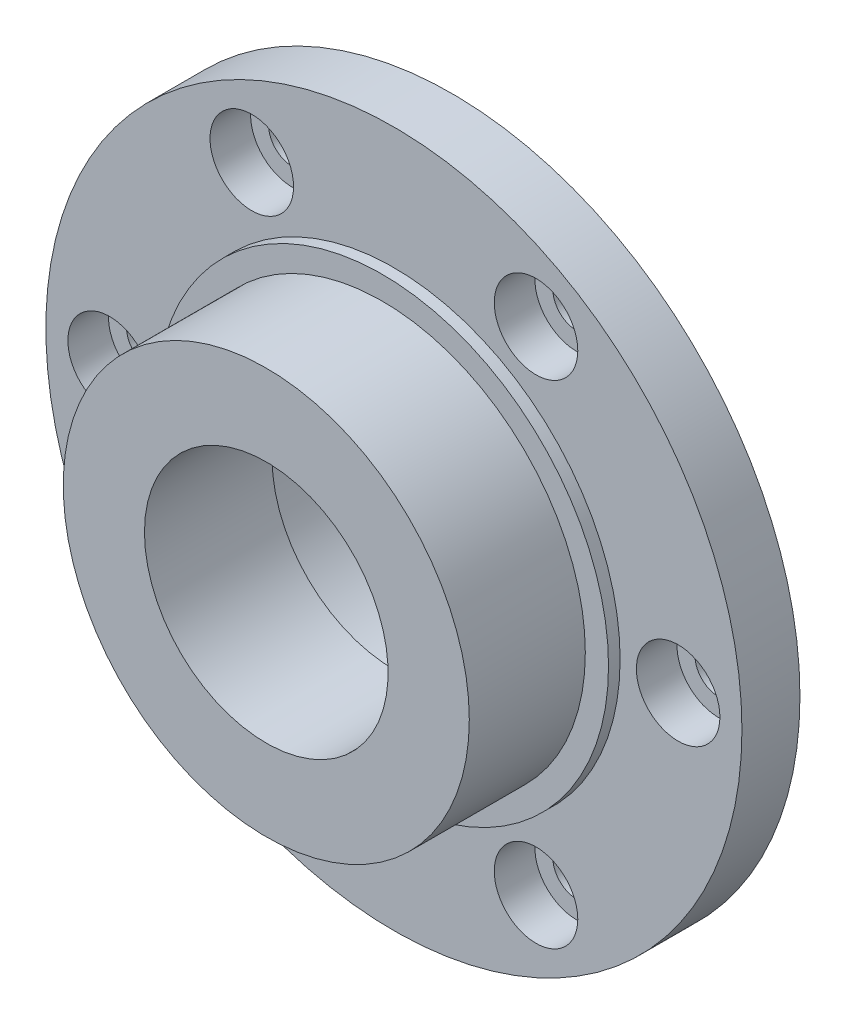
SolidWorks part; units mm, degrees
ref_plane "Front Plane" through (0, 0, 0) normal (0, 0, 1) x (1, 0, 0)
ref_plane "Top Plane" through (0, 0, 0) normal (0, 1, 0) x (1, 0, 0)
ref_plane "Right Plane" through (0, 0, 0) normal (1, 0, 0) x (0, 0, -1)
sketch "Sketch1" plane through (0, 0, 0) normal (0, 0, 1) x (1, 0, 0)
  circle A0 centre (0, 0) radius 30
  dimension "D1" = 60
extrude "Boss-Extrude1" add sketch "Sketch1" along normal blind 5
sketch "Sketch2" plane through (0, 0, 5) normal (0, 0, 1) x (1, 0, 0)
  circle A0 centre (0, 0) radius 19.5
  dimension "D1" = 39
extrude "Boss-Extrude2" add sketch "Sketch2" along normal blind 1
sketch "Sketch3" plane through (0, 0, 6) normal (0, 0, 1) x (1, 0, 0)
  circle A0 centre (0, 0) radius 17.5
  dimension "D1" = 35
extrude "Boss-Extrude3" add sketch "Sketch3" along normal blind 10
sketch "Sketch5" plane through (0, 0, 5) normal (0, 0, 1) x (1, 0, 0)
  line L0 (0, 0) -> (44.5119, 0) construction
  circle A0 centre (0, 0) radius 24.5 construction
  circle A2 centre (24.5, 0) radius 2.05
  circle A3 centre (12.25, -21.2176) radius 2.05
  circle A4 centre (-12.25, -21.2176) radius 2.05
  circle A5 centre (-24.5, 0) radius 2.05
  circle A6 centre (-12.25, 21.2176) radius 2.05
  circle A7 centre (12.25, 21.2176) radius 2.05
  point P19 (0, 0)
  dimension "D1" = 49
  dimension "D2" = 4.1
  dimension "D3" = 6
extrude "Cut-Extrude1" cut sketch "Sketch5" against normal through all
sketch "Sketch6" plane through (0, 0, 5) normal (0, 0, 1) x (1, 0, 0)
  circle A0 centre (0, 0) radius 24.5 construction
  circle A1 centre (24.5, 0) radius 3.6
  circle A2 centre (12.25, -21.2176) radius 3.6
  circle A3 centre (-12.25, -21.2176) radius 3.6
  circle A4 centre (-24.5, 0) radius 3.6
  circle A5 centre (-12.25, 21.2176) radius 3.6
  circle A6 centre (12.25, 21.2176) radius 3.6
  point P18 (0, 0)
  dimension "D1" = 7.2
  dimension "D2" = 6
extrude "Cut-Extrude2" cut sketch "Sketch6" against normal blind 3.5
sketch "Sketch9" plane through (0, 0, 0) normal (0, 0, -1) x (-1, 0, 0)
  circle A0 centre (0, 0) radius 5.5
  dimension "D1" = 11
extrude "Cut-Extrude5" cut sketch "Sketch9" against normal blind 4
sketch "Sketch7" plane through (0, 0, 0) normal (0, 0, -1) x (-1, 0, 0)
  circle A0 centre (0, 0) radius 12.025
  dimension "D1" = 24.05
extrude "Cut-Extrude3" cut sketch "Sketch7" against normal blind 5
sketch "Sketch8" plane through (0, 0, 5) normal (0, 0, -1) x (-1, 0, 0)
  circle A0 centre (0, 0) radius 10.5
  dimension "D1" = 21
extrude "Cut-Extrude4" cut sketch "Sketch8" against normal through all
